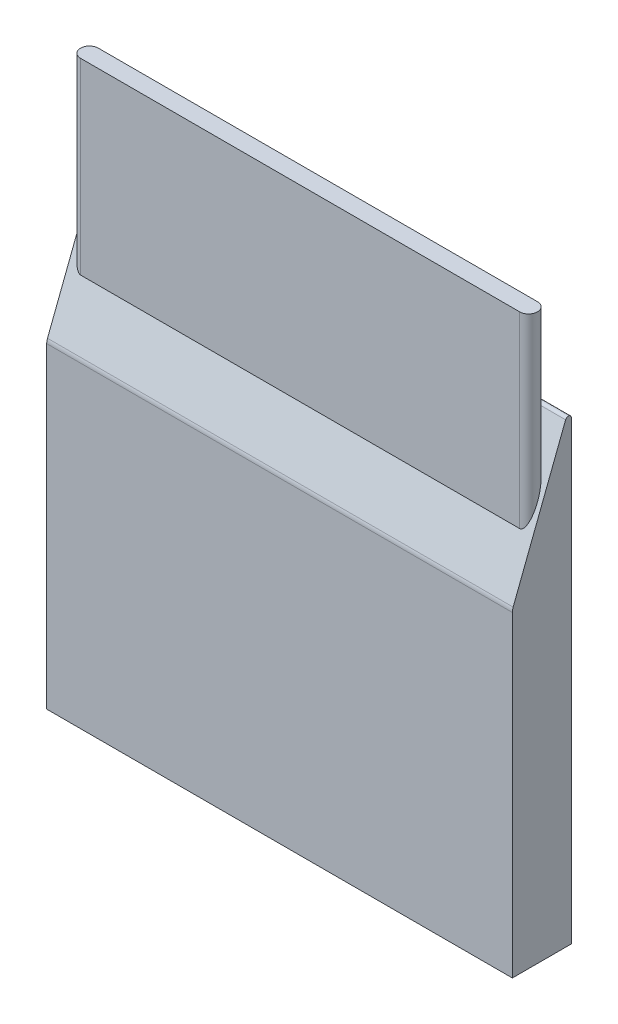
SolidWorks part; units mm, degrees
ref_plane "Alzado" through (0, 0, 0) normal (0, 0, 1) x (1, 0, 0)
ref_plane "Planta" through (0, 0, 0) normal (0, 1, 0) x (1, 0, 0)
ref_plane "Vista lateral" through (0, 0, 0) normal (1, 0, 0) x (0, 0, -1)
sketch "Croquis1" plane through (0, 0, 0) normal (0, 0, 1) x (1, 0, 0)
  line L1 (-11.6842, 19.8591) -> (67.3158, 19.8591)
  line L2 (-11.6842, 19.8591) -> (-11.6842, -60.1409)
  line L3 (-11.6842, -60.1409) -> (67.3158, -60.1409)
  line L4 (67.3158, 19.8591) -> (67.3158, -60.1409)
extrude "Saliente-Extruir1" add sketch "Croquis1" along normal blind 10
sketch "Croquis2" plane through (0, 19.8591, 0) normal (0, 1, 0) x (1, 0, 0)
  line L2 (65.0658, -5) -> (-9.4342, -5) construction
  line L3 (65.0658, -6.5) -> (-9.4342, -6.5)
  line L4 (65.0658, -3.5) -> (-9.4342, -3.5)
  arc A0 (65.0658, -6.5) -> (65.0658, -3.5) centre (65.0658, -5) ccw
  arc A1 (-9.4342, -3.5) -> (-9.4342, -6.5) centre (-9.4342, -5) ccw
  point P6 (27.8158, -5)
sketch "Croquis3" plane through (67.3158, 0, 0) normal (1, 0, 0) x (0, 0, -1)
  line L0 (-10, 19.8591) -> (-10, -6.0609)
  line L3 (-10, 19.8591) -> (0, 19.8591)
  line L4 (-10, -60.1409) -> (-10, 19.8591) construction
  line L6 (-10, -6.0609) -> (0, 19.8591)
extrude "Cortar-Extruir2" cut sketch "Croquis3" against normal blind 80
fillet "Redondeo3" radius 0.5 1 edges at (27.8158, 19.8591, 0)
fillet "Redondeo4" radius 2 1 edges at (27.8158, -6.0609, 10)
extrude "Saliente-Extruir2" add sketch "Croquis2" along normal blind 15 and the other way blind 20 separate body
